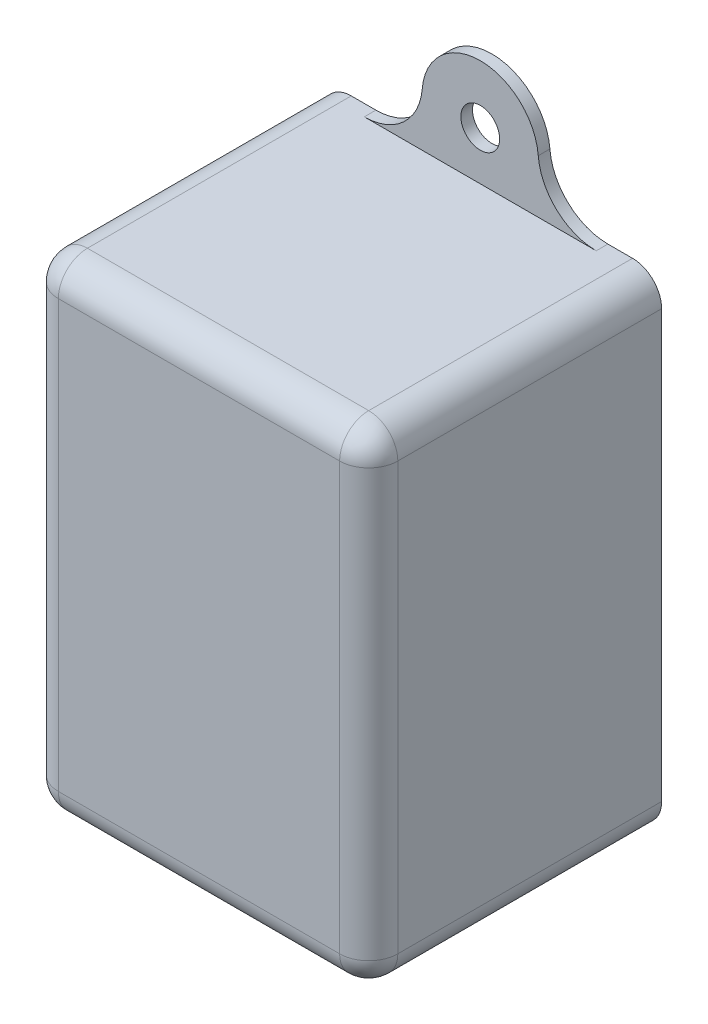
SolidWorks part; units mm, degrees
ref_plane "前视基准面" through (0, 0, 0) normal (0, 0, 1) x (1, 0, 0)
ref_plane "上视基准面" through (0, 0, 0) normal (0, 1, 0) x (1, 0, 0)
ref_plane "右视基准面" through (0, 0, 0) normal (1, 0, 0) x (0, 0, -1)
sketch "草图1" plane through (0, 0, 0) normal (0, 0, 1) x (1, 0, 0)
  line L0 (-11.9583, 25) -> (-17.5, 25)
  line L1 (-17.5, 25) -> (-17.5, -25)
  line L3 (17.5, -25) -> (17.5, 25)
  line L4 (-62.2008, 0) -> (42.7389, 0) construction
  line L5 (0, 66.4186) -> (0, -56.2887) construction
  line L6 (11.9583, 25) -> (17.5, 25)
  line L7 (-11.9583, -25) -> (-17.5, -25)
  line L8 (11.9583, -25) -> (17.5, -25)
  circle A0 centre (0, 30) radius 2
  circle A1 centre (0, -30) radius 2
  arc A2 (-5.9791, 30.5) -> (-11.9583, 25) centre (-11.9583, 31) cw
  arc A3 (5.9791, 30.5) -> (11.9583, 25) centre (11.9583, 31) ccw
  arc A4 (5.9791, -30.5) -> (11.9583, -25) centre (11.9583, -31) cw
  arc A5 (-5.9791, -30.5) -> (-11.9583, -25) centre (-11.9583, -31) ccw
  arc A6 (5.9791, 30.5) -> (-5.9791, 30.5) centre (0, 30) ccw
  arc A7 (5.9791, -30.5) -> (-5.9791, -30.5) centre (0, -30) cw
  dimension "D3" = 4
  dimension "D4" = 6
  dimension "D6" = 60
  dimension "D2" = 6
  dimension "D1" = 35
  dimension "D5" = 50
extrude "拉伸1" add sketch "草图1" along normal blind 1.2
sketch "草图5" plane through (0, 0, 1.2) normal (0, 0, 1) x (1, 0, 0)
  line L1 (-17.5, 25) -> (17.5, 25)
  line L2 (-17.5, 25) -> (-17.5, -25)
  line L3 (-17.5, -25) -> (17.5, -25)
  line L4 (17.5, 25) -> (17.5, -25)
extrude "拉伸2" add sketch "草图5" along normal blind 29
fillet "圆角1" radius 3 8 edges at (0, 25, 30.2) (17.5, 0, 30.2) (0, -25, 30.2) (-17.5, 0, 30.2) (-17.5, 25, 15.1) (-17.5, -25, 15.1) (17.5, -25, 15.1) (17.5, 25, 15.1)
